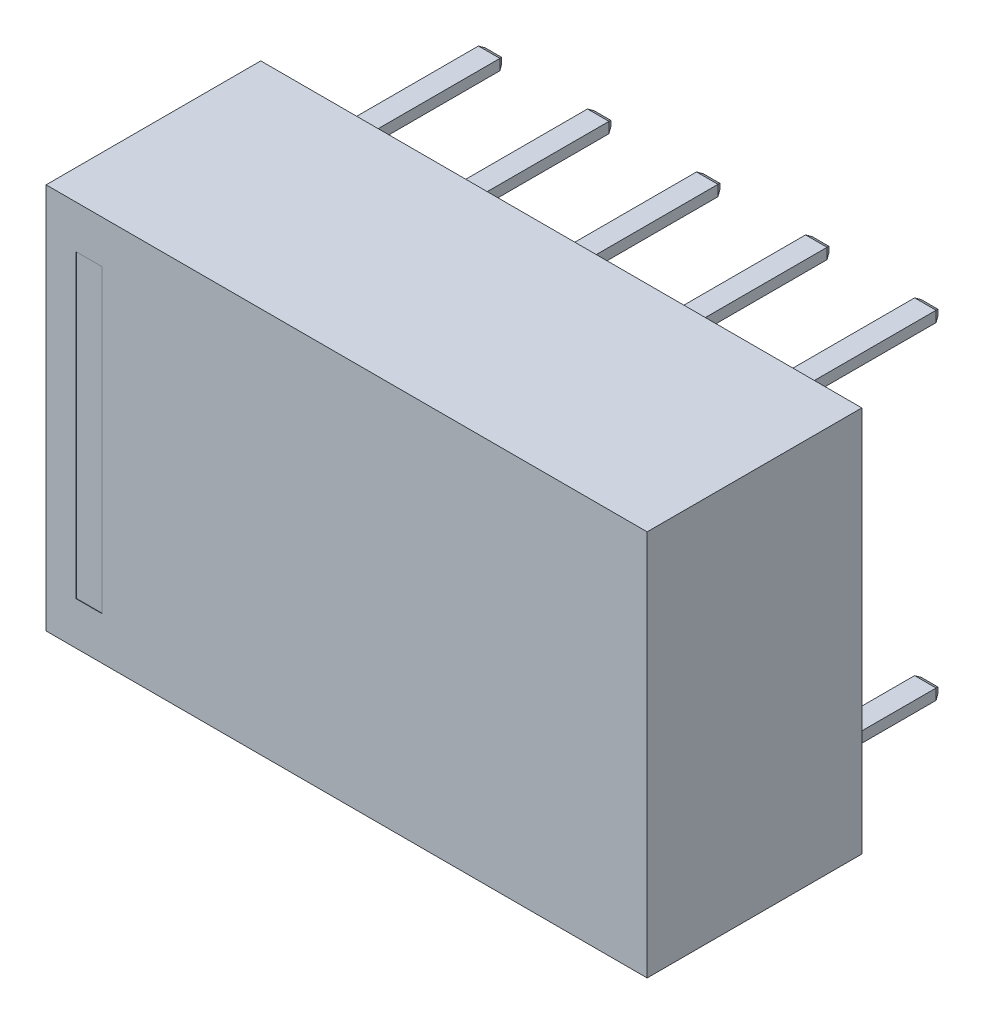
SolidWorks part; units mm, degrees
other "Детальный элемент1"
ref_plane "Спереди" through (0, 0, 0) normal (0, 0, 1) x (1, 0, 0)
ref_plane "Сверху" through (0, 0, 0) normal (0, 1, 0) x (1, 0, 0)
ref_plane "Справа" through (0, 0, 0) normal (1, 0, 0) x (0, 0, -1)
sketch "Эскиз1" plane through (0, 0, 0) normal (0, 0, 1) x (1, 0, 0)
  line L1 (-7, -4.5) -> (7, -4.5)
  line L2 (-7, -4.5) -> (-7, 4.5)
  line L3 (-7, 4.5) -> (7, 4.5)
  line L4 (7, -4.5) -> (7, 4.5)
  line L5 (-7, -4.5) -> (7, 4.5) construction
  line L6 (-7, 4.5) -> (7, -4.5) construction
  point P0 (0, 0)
  dimension "D1" = 14
  dimension "D2" = 9
extrude "Бобышка-Вытянуть1" add sketch "Эскиз1" along normal blind 5
ref_plane "Плоскость1" through (0, 0, 0) normal (0, 1, 0) x (1, 0, 0)
sketch "Эскиз3" plane through (0, 0, 5) normal (0, 0, 1) x (1, 0, 0)
  line L0 (2.75, 0) -> (-2.75, 0) construction
  line L1 (-5.7, -3.5) -> (-6.3, -3.5)
  line L2 (-5.7, -3.5) -> (-5.7, 3.5)
  line L3 (-5.7, 3.5) -> (-6.3, 3.5)
  line L4 (-6.3, -3.5) -> (-6.3, 3.5)
  line L5 (-5.7, -3.5) -> (-6.3, 3.5) construction
  line L6 (-5.7, 3.5) -> (-6.3, -3.5) construction
  line L7 (-7, 4.5) -> (-7, -4.5) construction
  point P0 (-6, 0)
  point P5 (0, 0)
  point P8 (0, 0)
  dimension "D1" = 7
  dimension "D2" = 0.6
  dimension "D3" = 1
extrude "Вырез-Вытянуть1" cut sketch "Эскиз3" against normal blind 0.01
sketch "Эскиз4" plane through (0, 0, 0) normal (0, 0, -1) x (-1, 0, 0)
  line L2 (5.33, -3.935) -> (4.83, -3.935)
  line L3 (5.33, -3.935) -> (5.33, -3.685)
  line L4 (5.33, -3.685) -> (4.83, -3.685)
  line L5 (4.83, -3.935) -> (4.83, -3.685)
  line L6 (5.33, -3.935) -> (4.83, -3.685) construction
  line L7 (5.33, -3.685) -> (4.83, -3.935) construction
  point P0 (5.08, -3.81)
  point P7 (0, 0)
  dimension "D3" = 0.25
  dimension "D1" = 5.08
  dimension "D2" = 3.81
  dimension "D4" = 0.5
extrude "Бобышка-Вытянуть2" add sketch "Эскиз4" along normal blind 3.5
chamfer "Фаска1" distance 0.1 angle 30 4 edges at (-4.83, -3.81, -3.5) (-5.08, -3.935, -3.5) (-5.33, -3.81, -3.5) (-5.08, -3.685, -3.5)
pattern_linear "Линейный массив1" count 5 spacing 2.54 along (1, 0, 0) count 2 spacing 7.62 along (0, 1, 0) of "Фаска1", "Бобышка-Вытянуть2"
